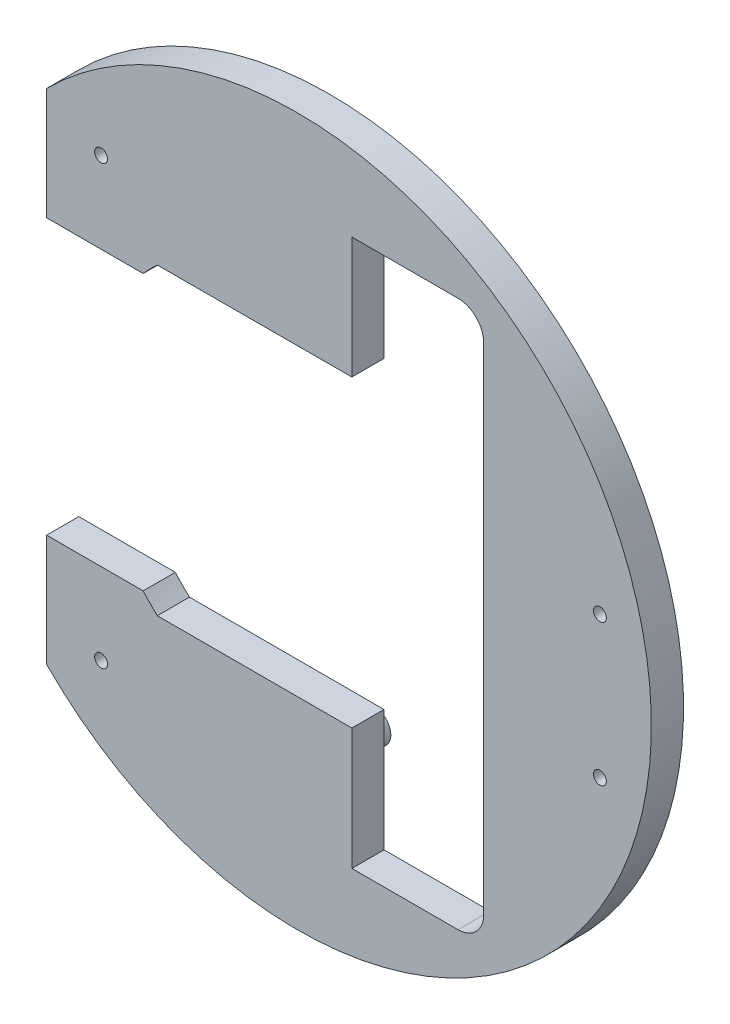
SolidWorks part; units mm, degrees
ref_plane "Front Plane" through (0, 0, 0) normal (0, 0, 1) x (1, 0, 0)
ref_plane "Top Plane" through (0, 0, 0) normal (0, 1, 0) x (1, 0, 0)
ref_plane "Right Plane" through (0, 0, 0) normal (1, 0, 0) x (0, 0, -1)
sketch "Sketch1" plane through (0, 0, 0) normal (0, 0, 1) x (1, 0, 0)
  line L0 (8.4443, -42.5) -> (8.4443, -23.6022)
  line L1 (8.4443, -23.6022) -> (-13.0476, -23.6022)
  line L2 (-13.0476, -23.6022) -> (-21.7987, -23.6022)
  line L3 (-21.7987, 23.6022) -> (8.4443, 23.6534)
  line L4 (8.4443, 23.6534) -> (8.4443, 42.5)
  line L9 (-13.0476, 29.36) -> (-13.0476, 41.3197)
  line L10 (8.4443, 42.5) -> (24.944, 42.5)
  line L11 (28.944, 38.5) -> (28.944, -38.5)
  line L12 (24.944, -42.5) -> (8.4443, -42.5)
  line L13 (-13.0476, -41.3197) -> (-13.0476, -29.36)
  line L14 (-24, -21.36) -> (-39, -21.36)
  line L15 (-39, -21.36) -> (-39, -38.7814)
  line L16 (-39, 38.7814) -> (-39, 21.36)
  line L17 (-39, 21.36) -> (-24, 21.36)
  line L19 (8.4443, 42.5) -> (24.944, 42.5)
  line L20 (28.944, 38.5) -> (28.944, -38.5)
  line L21 (24.944, -42.5) -> (8.4443, -42.5)
  line L23 (-24, -21.36) -> (-39, -21.36)
  line L24 (-39, -21.36) -> (-39, -38.7814)
  line L25 (-39, 38.7814) -> (-39, 21.36)
  line L26 (-39, 21.36) -> (-24, 21.36)
  arc A7 (-13.0476, 29.36) -> (-24, 21.36) centre (0, 0) ccw
  arc A8 (8.4443, 42.5) -> (-13.0476, 41.3197) centre (0, 0) ccw
  arc A9 (28.944, 38.5) -> (24.944, 42.5) centre (24.944, 38.5) ccw
  arc A10 (24.944, -42.5) -> (28.944, -38.5) centre (24.944, -38.5) ccw
  arc A11 (-13.0476, -41.3197) -> (8.4443, -42.5) centre (0, 0) ccw
  arc A12 (-24, -21.36) -> (-13.0476, -29.36) centre (0, 0) ccw
  arc A13 (-39, -38.7814) -> (-39, 38.7814) centre (0, 0) ccw
  arc A14 (-21.7987, 23.6022) -> (-24, 21.36) centre (0, 0) ccw
  arc A16 (28.944, 38.5) -> (24.944, 42.5) centre (24.944, 38.5) ccw
  arc A17 (24.944, -42.5) -> (28.944, -38.5) centre (24.944, -38.5) ccw
  arc A19 (-24, -21.36) -> (-21.7987, -23.6022) centre (0, 0) ccw
  arc A20 (-39, -38.7814) -> (-39, 38.7814) centre (0, 0) ccw
  point P27 (0, 0)
  point P32 (0, 0)
  dimension "D1" = 0
extrude "Boss-Extrude1" add sketch "Sketch1" along normal blind 5
sketch "Sketch2" plane through (0, 0, 0) normal (0, 0, -1) x (-1, 0, 0)
  circle A0 centre (0, -33.5) radius 2.5
  circle A1 centre (0, 33.5) radius 2.5
extrude "Boss-Extrude2" add sketch "Sketch2" along normal blind 7
sketch "Sketch3" plane through (0, 0, 5) normal (0, 0, 1) x (1, 0, 0)
  line L0 (47, -11) -> (47, 11) construction
  line L1 (47, 11) -> (24.944, 42.5) construction
  line L2 (28.944, 38.5) -> (28.944, -38.5) construction
  line L3 (57.6175, -37.7066) -> (57.2572, -37.5625) construction
  line L4 (47, -11) -> (24.944, -42.5) construction
  line L5 (-39, -38.7814) -> (-30.5379, -34) construction
  line L6 (-30.5379, -34) -> (-30.5379, 34) construction
  line L7 (-30.5379, 34) -> (-39, 38.7814) construction
  circle A0 centre (-30.5379, -34) radius 1
  circle A1 centre (-30.5379, 34) radius 1
  circle A2 centre (47, 11) radius 1
  circle A3 centre (47, -11) radius 1
  arc A5 (24.944, -42.5) -> (28.944, -38.5) centre (24.944, -38.5) ccw construction
  dimension "D1" = 2
  dimension "D2" = 22
  dimension "D3" = 68
extrude "Cut-Extrude1" cut sketch "Sketch3" against normal up to surface (5 mm away) up to face at (2.5, 33.5, 0)
